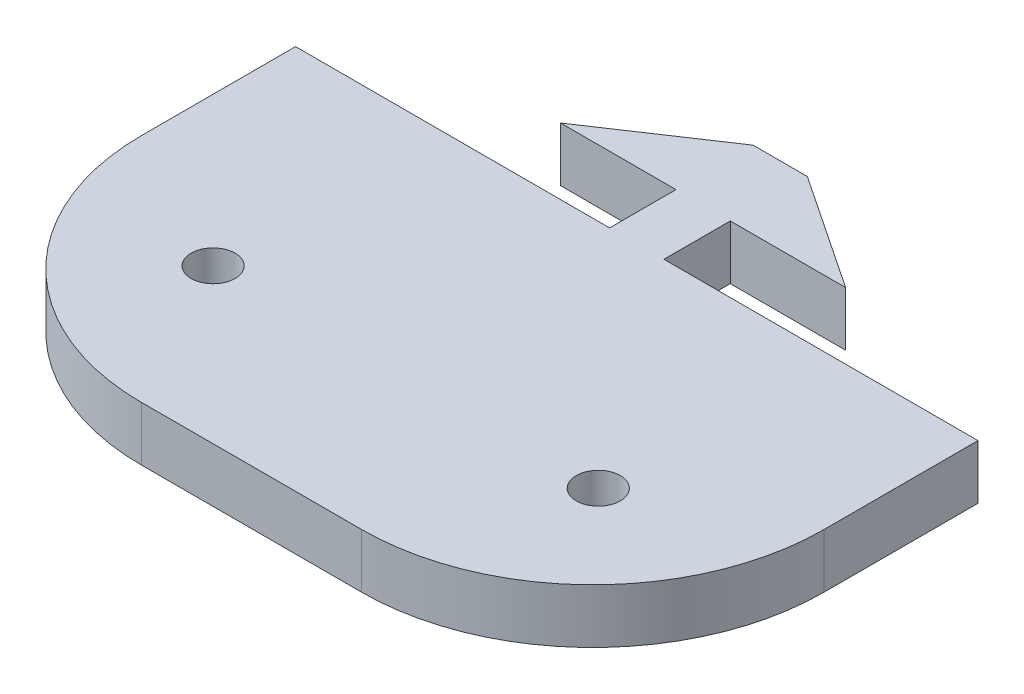
SolidWorks part; units mm, degrees
ref_plane "Front" through (0, 0, 0) normal (0, 0, 1) x (1, 0, 0)
ref_plane "Top" through (0, 0, 0) normal (0, 1, 0) x (1, 0, 0)
ref_plane "Right" through (0, 0, 0) normal (1, 0, 0) x (0, 0, -1)
sketch "Sketch1" plane through (0, 0, 0) normal (0, 1, 0) x (1, 0, 0)
  line L0 (-1.7907, 2.1875) -> (-9.398, 2.1875)
  line L2 (-1.7907, -2.1875) -> (-1.7907, 2.1875)
  line L4 (1.7907, -2.1875) -> (1.7907, 2.1875)
  line L7 (-9.398, 2.1875) -> (-1.7907, 7.2675)
  line L8 (-1.7907, 7.2675) -> (1.7907, 7.2675)
  line L9 (1.7907, 7.2675) -> (9.398, 2.1875)
  line L10 (9.398, 2.1875) -> (1.7907, 2.1875)
  line L11 (1.7907, -2.1875) -> (22.5, -2.1875)
  line L12 (-1.7907, -2.1875) -> (-22.5, -2.1875)
  line L13 (-22.5, -2.1875) -> (-22.5, -27.5875)
  line L14 (-22.5, -27.5875) -> (22.5, -27.5875)
  line L15 (22.5, -27.5875) -> (22.5, -2.1875)
  line L16 (22.5, -2.1875) -> (1.7907, -2.1875)
  point P0 (0, 0)
  point P17 (0, 7.2675)
  point P19 (0, -27.5875)
  point P24 (1.7907, 0)
  dimension "D1" = 18.796
  dimension "D2" = 3.5814
  dimension "D3" = 45
  dimension "D4" = 25.4
  dimension "D5" = 5.08
  dimension "D7" = 4.375
extrude "Boss-Extrude1" add sketch "Sketch1" along normal blind 3.5814 contours L14 L15 L11 L4 L10 L9 L8 L7 L0 L2 L12 L13
sketch "Sketch2" plane through (0, 3.5814, 0) normal (0, 1, 0) x (1, 0, 0)
  line L0 (0, 0) -> (0, -15.3387) construction
  line L1 (1.7907, -2.1875) -> (22.5, -2.1875) construction
  circle A0 centre (-12.7, -17.4275) radius 1.45
  circle A1 centre (12.7, -17.4275) radius 1.45
  point P7 (0, 0)
  point P8 (0, 0)
  dimension "D1" = 2.9
  dimension "D2" = 12.7
  dimension "D3" = 15.24
extrude "Cut-Extrude1" cut sketch "Sketch2" against normal through all
fillet "Fillet1" radius 15.24 2 edges at (-22.5, 1.7907, 27.5875) (22.5, 1.7907, 27.5875)
